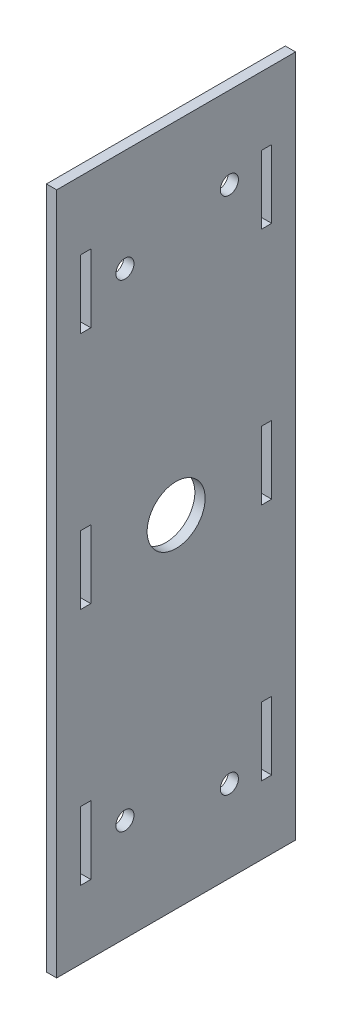
SolidWorks part; units mm, degrees
ref_plane "Front Plane" through (0, 0, 0) normal (1, 0, 0) x (0, 1, 0)
ref_plane "Top Plane" through (0, 0, 0) normal (0, 0, 1) x (0, 1, 0)
ref_plane "Right Plane" through (0, 0, 0) normal (0, 1, 0) x (-1, 0, 0)
sketch "Sketch1" plane through (0, 0, 0) normal (1, 0, 0) x (0, 1, 0)
  line L0 (0, 81.4023) -> (0, -114.8153) construction
  line L1 (-100, 35) -> (100, 35)
  line L2 (-100, 35) -> (-100, -35)
  line L3 (-100, -35) -> (100, -35)
  line L4 (100, 35) -> (100, -35)
  line L5 (-80, -25) -> (-60, -25)
  line L6 (-80, -25) -> (-80, -28)
  line L7 (-80, -28) -> (-60, -28)
  line L8 (-60, -25) -> (-60, -28)
  line L9 (80, -28) -> (60, -28)
  line L10 (60, -25) -> (60, -28)
  line L11 (80, -25) -> (60, -25)
  line L12 (80, -25) -> (80, -28)
  line L13 (-217.085, 0) -> (250.2284, 0) construction
  line L14 (-10, -25) -> (10, -25)
  line L15 (-10, -25) -> (-10, -28)
  line L16 (-10, -28) -> (10, -28)
  line L17 (10, -25) -> (10, -28)
  line L18 (80, 25) -> (80, 28)
  line L19 (80, 25) -> (60, 25)
  line L20 (60, 25) -> (60, 28)
  line L21 (80, 28) -> (60, 28)
  line L22 (-10, 28) -> (10, 28)
  line L23 (10, 25) -> (10, 28)
  line L24 (-10, 25) -> (10, 25)
  line L25 (-10, 25) -> (-10, 28)
  line L26 (-80, 28) -> (-60, 28)
  line L27 (-60, 25) -> (-60, 28)
  line L28 (-80, 25) -> (-60, 25)
  line L29 (-80, 25) -> (-80, 28)
  circle A0 centre (0, 0) radius 8.5
  circle A1 centre (-76, -15.6) radius 2.65
  circle A3 centre (76, -15.6) radius 2.65
  circle A4 centre (-70, 15) radius 2.65
  circle A5 centre (70, 15) radius 2.65
  point P4 (0, 35)
  point P6 (-100, 0)
  point P27 (0, -25)
  point P28 (10, -26.5)
  point P29 (60, -26.5)
  dimension "D1" = 17
  dimension "D2" = 5.3
  dimension "D13" = 5.3
  dimension "D3" = 3
  dimension "D4" = 20
  dimension "D5" = 20
  dimension "D6" = 10
  dimension "D7" = 76
  dimension "D8" = 15.6
  dimension "D9" = 20
  dimension "D10" = 3
  dimension "D11" = 200
  dimension "D12" = 70
  dimension "D14" = 10
  dimension "D15" = 30
extrude "Boss-Extrude1" add sketch "Sketch1" along normal blind 3
